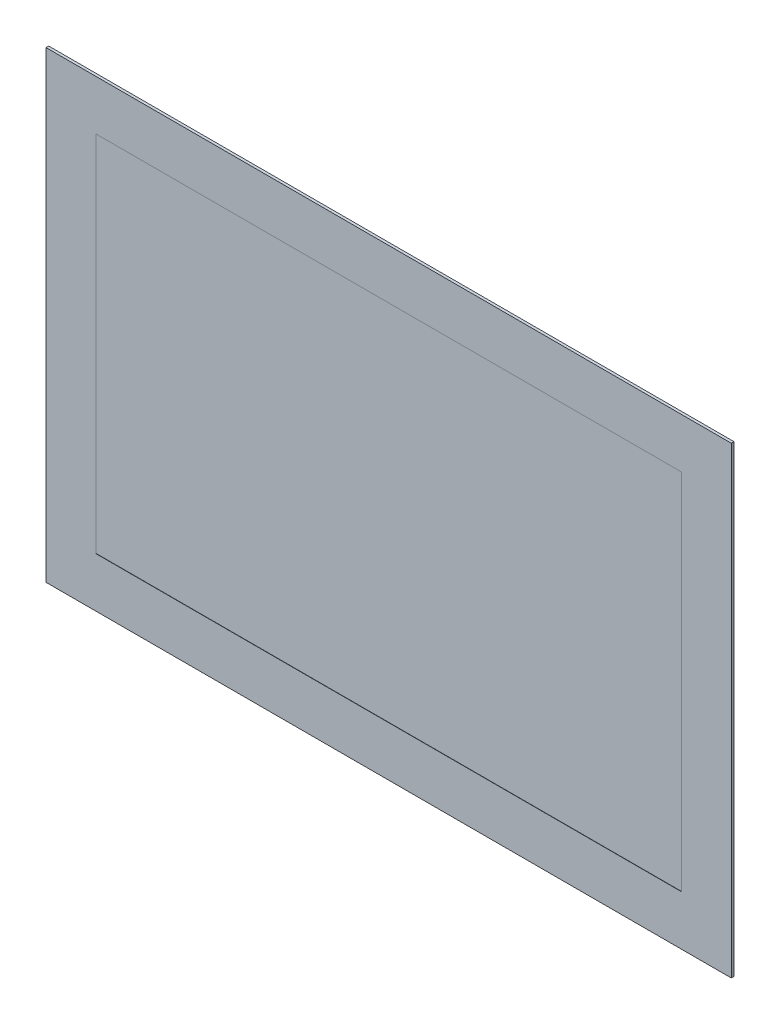
SolidWorks part; units mm, degrees
ref_plane "Top Plane" through (0, 0, 0) normal (0, 0, 1) x (1, 0, 0)
ref_plane "Right Plane" through (0, 0, 0) normal (0, 1, 0) x (1, 0, 0)
ref_plane "Front Plane" through (0, 0, 0) normal (1, 0, 0) x (0, 0, -1)
sketch "Sketch1" plane through (0, 0, 0) normal (0, 0, 1) x (1, 0, 0)
  line L1 (-127.25, 86) -> (127.25, 86)
  line L2 (-127.25, 86) -> (-127.25, -86)
  line L3 (-127.25, -86) -> (127.25, -86)
  line L4 (127.25, 86) -> (127.25, -86)
  line L5 (-127.25, 86) -> (127.25, -86) construction
  line L6 (-127.25, -86) -> (127.25, 86) construction
  point P4 (0, 0)
  dimension "D1" = 254.5
  dimension "D2" = 172
extrude "Boss-Extrude1" add sketch "Sketch1" along normal blind 1
sketch "Sketch2" plane through (0, 0, 0) normal (0, 0, -1) x (-1, 0, 0)
  line L0 (0, 71.5) -> (0, -76.5) construction
  line L1 (115, -76.5) -> (-115, -76.5)
  line L2 (115, -76.5) -> (115, 71.5)
  line L3 (115, 71.5) -> (-115, 71.5)
  line L4 (-115, -76.5) -> (-115, 71.5)
  line L5 (-127.25, 86) -> (127.25, 86) construction
  point P4 (0, 0)
  dimension "D1" = 230
  dimension "D2" = 148
  dimension "D3" = 14.5
extrude "Boss-Extrude2" add sketch "Sketch2" along normal blind 9
sketch "Sketch3" plane through (0, 0, -9) normal (0, 0, -1) x (-1, 0, 0)
  line L0 (115, 71.5) -> (-115, 71.5) construction
  line L1 (29, -26.5) -> (-29, -26.5) construction
  line L2 (29, -26.5) -> (29, 22.5) construction
  line L3 (29, 22.5) -> (-29, 22.5) construction
  line L4 (-29, -26.5) -> (-29, 22.5) construction
  line L5 (29, -26.5) -> (-29, 22.5) construction
  line L6 (29, 22.5) -> (-29, -26.5) construction
  line L7 (0, -2) -> (0, 0) construction
  circle A0 centre (29, -26.5) radius 1.75
  circle A1 centre (-29, -26.5) radius 1.75
  circle A2 centre (-29, 22.5) radius 1.75
  circle A3 centre (29, 22.5) radius 1.75
  point P4 (0, -2)
  dimension "D4" = 3.5
  dimension "D1" = 49
  dimension "D2" = 49
  dimension "D3" = 58
extrude "Cut-Extrude1" cut sketch "Sketch3" against normal blind 2
sketch "Sketch4" plane through (0, 0, 1) normal (0, 0, 1) x (1, 0, 0)
  line L0 (127.25, 86) -> (-127.25, 86) construction
  line L1 (108.75, -67.5) -> (-108.75, -67.5)
  line L2 (108.75, -67.5) -> (108.75, 67.5)
  line L3 (108.75, 67.5) -> (-108.75, 67.5)
  line L4 (-108.75, -67.5) -> (-108.75, 67.5)
  line L5 (-108.75, 67.5) -> (108.75, -67.5) construction
  line L6 (-127.25, 86) -> (-127.25, -86) construction
  point P9 (52.6517, -32.6804)
  dimension "D1" = 18.5
  dimension "D2" = 18.5
extrude "Cut-Extrude2" cut sketch "Sketch4" against normal blind 0.1
